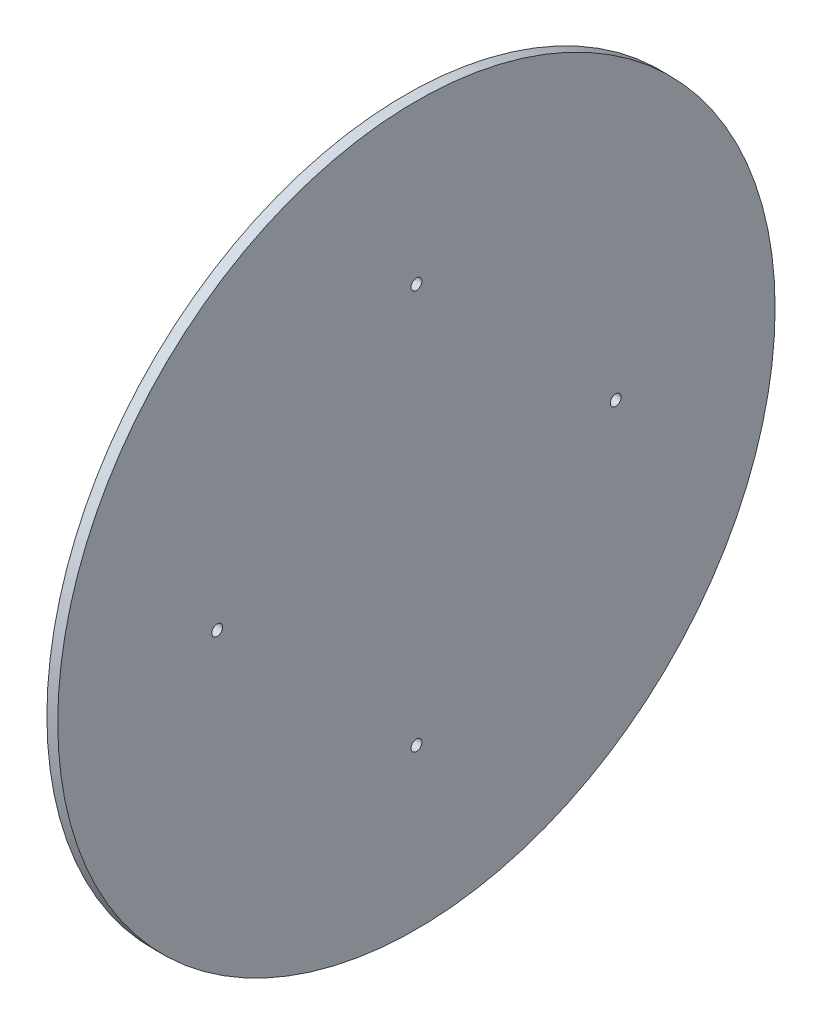
SolidWorks part; units mm, degrees
ref_plane "Front Plane" through (0, 0, 0) normal (0, 0, 1) x (1, 0, 0)
ref_plane "Top Plane" through (0, 0, 0) normal (0, 1, 0) x (1, 0, 0)
ref_plane "Right Plane" through (0, 0, 0) normal (1, 0, 0) x (0, 0, -1)
sketch "Sketch1" plane through (0, 0, 0) normal (1, 0, 0) x (0, 0, -1)
  line L0 (0, 0) -> (0, 55)
  line L1 (0, 55) -> (0.0058, 55.2062)
  line L2 (0, 0) -> (55, 0)
  line L3 (0, 0) -> (0, -55)
  line L4 (0, 0) -> (-55, 0)
  circle A0 centre (0, 0) radius 99
  circle A1 centre (-55, 0) radius 1.5
  circle A2 centre (0.0058, 55.2062) radius 1.5
  circle A3 centre (55, 0) radius 1.5
  circle A4 centre (0, -55) radius 1.5
extrude "Boss-Extrude2" add sketch "Sketch1" along normal blind 3
